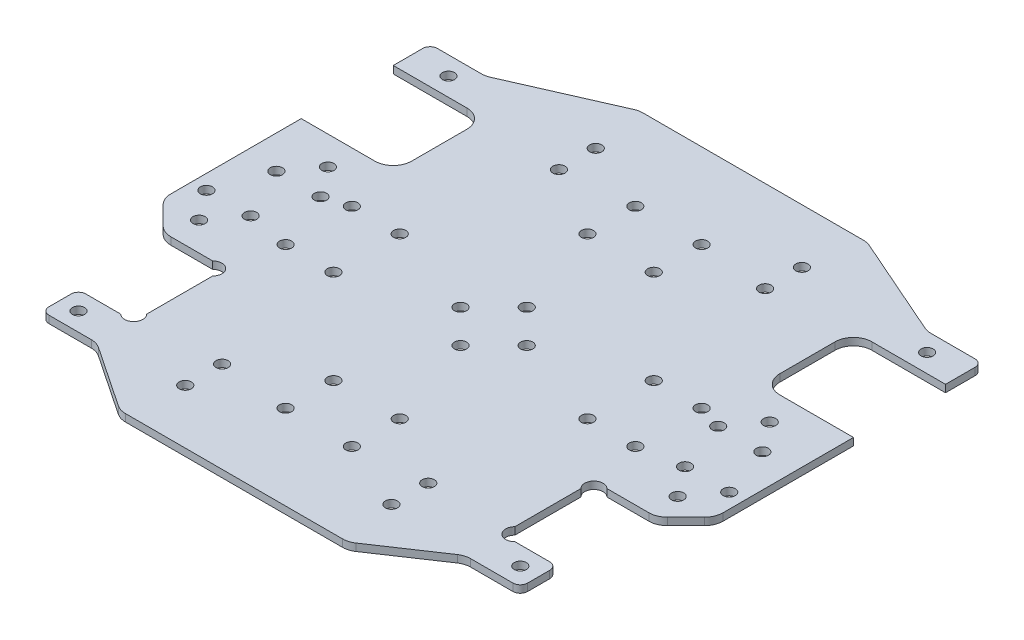
SolidWorks part; units mm, degrees
ref_plane "前视基准面" through (0, 0, 0) normal (0, 0, 1) x (1, 0, 0)
ref_plane "上视基准面" through (0, 0, 0) normal (0, 1, 0) x (1, 0, 0)
ref_plane "右视基准面" through (0, 0, 0) normal (1, 0, 0) x (0, 0, -1)
sketch "草图1" plane through (0, 0, 0) normal (0, 1, 0) x (1, 0, 0)
  line L1 (-75, -70.5) -> (75, -70.5)
  line L2 (-75, -70.5) -> (-75, 70.5)
  line L3 (-75, 70.5) -> (75, 70.5)
  line L4 (75, -70.5) -> (75, 70.5)
  line L5 (-75, -70.5) -> (75, 70.5) construction
  line L6 (-75, 70.5) -> (75, -70.5) construction
  point P0 (0, 0)
  dimension "D1" = 141
  dimension "D2" = 150
extrude "凸台-拉伸1" add sketch "草图1" along normal blind 2
sketch "草图2" plane through (0, 2, 0) normal (0, 1, 0) x (1, 0, 0)
  line L0 (-60, -11) -> (-65, -11) construction
  line L1 (-60, -11) -> (60, -11) construction
  line L2 (-60, -11) -> (-60, 11) construction
  line L3 (-60, 11) -> (60, 11) construction
  line L4 (60, -11) -> (60, 11) construction
  line L5 (-60, -11) -> (60, 11) construction
  line L6 (-60, 11) -> (60, -11) construction
  line L11 (-75, 70.5) -> (-75, -70.5) construction
  line L12 (-66, 7) -> (-54, 7) construction
  line L13 (-71, -15) -> (-59, -15) construction
  line L14 (-66, 7) -> (-66, 15) construction
  line L15 (-66, 15) -> (-54, 15) construction
  line L16 (-54, 7) -> (-54, 15) construction
  line L17 (-66, 7) -> (-54, 15) construction
  line L18 (-66, 15) -> (-54, 7) construction
  line L19 (-71, -15) -> (-71, -7) construction
  line L20 (-71, -7) -> (-59, -7) construction
  line L21 (-59, -15) -> (-59, -7) construction
  line L22 (-71, -15) -> (-59, -7) construction
  line L23 (-71, -7) -> (-59, -15) construction
  circle A4 centre (-60, 15) radius 1.65
  circle A5 centre (-66, 7) radius 1.65
  circle A6 centre (-54, 7) radius 1.65
  circle A7 centre (-71, -7) radius 1.65
  circle A8 centre (-59, -7) radius 1.65
  circle A9 centre (-65, -15) radius 1.65
  point P0 (0, 0)
  point P14 (-60, 0)
  dimension "D5" = 3.3
  dimension "D1" = 12
  dimension "D2" = 8
  dimension "D3" = 15
  dimension "D4" = 15
  dimension "D6" = 5
  dimension "D7" = 8
  dimension "D8" = 12
extrude "切除-拉伸1" cut sketch "草图2" against normal up to next
sketch "草图9" plane through (0, 2, 0) normal (0, 1, 0) x (1, 0, 0)
  line L0 (0, 22.75) -> (0, -22.75) construction
  line L1 (-75, -70.5) -> (-50, -70.5)
  line L2 (-75, -70.5) -> (-75, -22.75)
  line L3 (-75, -22.75) -> (-50, -22.75)
  line L4 (-50, -70.5) -> (-50, -22.75)
  line L5 (75, -70.5) -> (50, -70.5)
  line L6 (75, -70.5) -> (75, -22.75)
  line L7 (75, -22.75) -> (50, -22.75)
  line L8 (50, -70.5) -> (50, -22.75)
  point P14 (0, 0)
  dimension "D1" = 45.5
  dimension "D2" = 100
extrude "切除-拉伸5" cut sketch "草图9" against normal up to next
sketch "草图10" plane through (0, 2, 0) normal (0, 1, 0) x (1, 0, 0)
  line L0 (-75, 70.5) -> (-31, 70.5)
  line L1 (75, 70.5) -> (-75, 70.5) construction
  line L2 (-31, 70.5) -> (-60, 57.75)
  line L3 (-60, 57.75) -> (-75, 57.75)
  line L4 (-75, 70.5) -> (-75, -22.75) construction
  line L5 (-75, 57.75) -> (-75, 70.5)
  line L6 (0, 70.5) -> (-31, 70.5) construction
  dimension "D1" = 15
  dimension "D2" = 12.75
  dimension "D3" = 31
extrude "切除-拉伸6" cut sketch "草图10" against normal up to next
mirror "镜向1" about plane through (0, 0, 0) normal (1, 0, 0) of "切除-拉伸6", "切除-拉伸1"
chamfer "倒角1" distance 8 angle 45 2 edges at (75, 1, 22.75) (-75, 1, 22.75)
sketch "草图11" plane through (0, 2, 0) normal (0, 1, 0) x (1, 0, 0)
  line L0 (-75, 57.75) -> (-75, -14.75) construction
  line L1 (-75, 47.75) -> (-50, 47.75)
  line L2 (-75, 47.75) -> (-75, 22.75)
  line L3 (-75, 22.75) -> (-50, 22.75)
  line L4 (-50, 47.75) -> (-50, 22.75)
  line L5 (-75, 57.75) -> (-60, 57.75) construction
  line L6 (0, 0) -> (0, 70.5) construction
  line L7 (31, 70.5) -> (-31, 70.5) construction
  line L8 (75, 22.75) -> (50, 22.75)
  line L9 (50, 47.75) -> (50, 22.75)
  line L10 (75, 47.75) -> (50, 47.75)
  line L11 (75, 47.75) -> (75, 22.75)
  dimension "D1" = 10
  dimension "D2" = 25
  dimension "D3" = 25
extrude "切除-拉伸7" cut sketch "草图11" against normal up to next
sketch "草图12" plane through (0, 2, 0) normal (0, 1, 0) x (1, 0, 0)
  line L0 (-75, 52.75) -> (-65, 52.75) construction
  line L1 (-75, 57.75) -> (-75, 47.75) construction
  line L2 (0, 0) -> (0, 70.5) construction
  line L3 (31, 70.5) -> (-31, 70.5) construction
  circle A0 centre (-65, 52.75) radius 1.65
  circle A1 centre (65, 52.75) radius 1.65
  dimension "D1" = 3.3
  dimension "D2" = 10
extrude "切除-拉伸8" cut sketch "草图12" against normal up to next
fillet "圆角1" radius 5 8 edges at (75, 1, 14.75) (67, 1, 22.75) (-67, 1, 22.75) (-75, 1, 14.75) (50, 1, -22.75) (50, 1, -47.75) (-50, 1, -22.75) (-50, 1, -47.75)
sketch "草图13" plane through (0, 2, 0) normal (0, 1, 0) x (1, 0, 0)
  line L0 (-50, -70.5) -> (-50, -57.75)
  line L1 (-50, -70.5) -> (-50, -22.75) construction
  line L2 (-50, -57.75) -> (-31, -70.5)
  line L3 (-50, -70.5) -> (50, -70.5) construction
  line L4 (-31, -70.5) -> (-50, -70.5)
  line L5 (31, -70.5) -> (-31, -70.5) construction
  point P11 (0, -70.5)
  dimension "D1" = 12.75
  dimension "D2" = 62
extrude "切除-拉伸9" cut sketch "草图13" against normal up to next
sketch "草图14" plane through (0, 0, 0) normal (0, 1, 0) x (1, 0, 0)
  line L1 (-50, -57.75) -> (-65, -57.75)
  line L2 (-50, -57.75) -> (-50, -47.75)
  line L3 (-50, -47.75) -> (-65, -47.75)
  line L4 (-65, -57.75) -> (-65, -47.75)
  dimension "D1" = 15
  dimension "D2" = 10
extrude "凸台-拉伸2" add sketch "草图14" along normal up to surface (2 mm away) up to face at (-65, 2, -51.1)
sketch "草图15" plane through (0, 2, 0) normal (0, 1, 0) x (1, 0, 0)
  line L0 (-65, -52.75) -> (-60, -52.75) construction
  line L1 (-65, -57.75) -> (-65, -47.75) construction
  circle A0 centre (-60, -52.75) radius 1.65
  dimension "D2" = 3.3
  dimension "D1" = 5
extrude "切除-拉伸10" cut sketch "草图15" against normal up to next
sketch "草图18" plane through (0, 2, 0) normal (0, 1, 0) x (1, 0, 0)
  line L0 (-51.7678, -45.9822) -> (-50, -47.75) construction
  line L1 (-51.7678, -24.5178) -> (-50, -22.75) construction
  line L2 (-50, -47.75) -> (-50, -22.75) construction
  circle A0 centre (-51.7678, -24.5178) radius 2.5
  circle A1 centre (-51.7678, -45.9822) radius 2.5
  dimension "10" = 5
  dimension "D1" = 45
  dimension "D2" = 45
extrude "切除-拉伸13" cut sketch "草图18" against normal up to next
sketch "草图19" plane through (0, 2, 0) normal (0, 1, 0) x (1, 0, 0)
  line L0 (0, 0) -> (-34.5, 0) construction
  line L1 (-34.5, 0) -> (-47.5, 0) construction
  line L2 (-47.5, 9) -> (-47.5, -9) construction
  line L3 (-34.5, 9) -> (-34.5, -9) construction
  line L4 (-47.5, -9) -> (-34.5, -9) construction
  circle A0 centre (-47.5, 9) radius 1.65
  circle A1 centre (-47.5, -9) radius 1.65
  circle A2 centre (-34.5, -9) radius 1.65
  circle A3 centre (-34.5, 9) radius 1.65
  point P6 (-47.5, 0)
  point P10 (-34.5, 0)
  dimension "D2" = 3.3
  dimension "D1" = 18
  dimension "D3" = 47.5
  dimension "D4" = 13
extrude "切除-拉伸14" cut sketch "草图19" against normal up to next
mirror "镜向2" about plane through (0, 0, 0) normal (1, 0, 0) of "切除-拉伸13", "切除-拉伸10", "切除-拉伸9", "凸台-拉伸2"
mirror "镜向4" about plane through (0, 0, 0) normal (1, 0, 0) of "切除-拉伸14"
sketch "草图20" plane through (0, 2, 0) normal (0, 1, 0) x (1, 0, 0)
  line L0 (0, 9) -> (0, -9) construction
  circle A0 centre (0, 9) radius 1.65
  circle A1 centre (0, -9) radius 1.65
  point P4 (0, 0)
  dimension "D2" = 3.3
  dimension "D1" = 18
extrude "切除-拉伸15" cut sketch "草图20" against normal up to next
fillet "圆角2" radius 2 6 edges at (75, 1, -57.75) (-75, 1, -57.75) (65, 1, 57.75) (65, 1, 47.75) (-65, 1, 57.75) (-65, 1, 47.75)
sketch "草图17" plane through (0, 2, 0) normal (0, 1, 0) x (1, 0, 0)
  line L0 (0, 0) -> (0, -50.75) construction
  line L2 (-28, -55.75) -> (28, -55.75) construction
  line L3 (-28, -55.75) -> (-28, -45.75) construction
  line L4 (-28, -45.75) -> (28, -45.75) construction
  line L5 (28, -55.75) -> (28, -45.75) construction
  line L6 (-28, -55.75) -> (28, -45.75) construction
  line L7 (-28, -45.75) -> (28, -55.75) construction
  circle A0 centre (-28, -45.75) radius 1.65
  circle A1 centre (-28, -55.75) radius 1.65
  circle A2 centre (28, -45.75) radius 1.65
  circle A3 centre (28, -55.75) radius 1.65
  dimension "D4" = 3.3
  dimension "D1" = 50.75
  dimension "D2" = 10
  dimension "D3" = 56
extrude "切除-拉伸12" cut sketch "草图17" against normal up to next
mirror "镜向3" about plane through (0, 0, 0) normal (0, 0, 1) of "切除-拉伸12"
fillet "圆角3" radius 5 8 edges at (50, 1, 57.75) (31, 1, 70.5) (-31, 1, 70.5) (-50, 1, 57.75) (60, 1, -57.75) (31, 1, -70.5) (-31, 1, -70.5) (-60, 1, -57.75)
sketch "草图21" plane through (0, 0, 0) normal (0, 0, 1) x (1, 0, 0)
  line L0 (0, 0) -> (0, 2) construction
  line L1 (-29.4778, 2) -> (29.4778, 2) construction
pattern_circular "阵列(圆周)1" count 2 every 90 about axis through (0, 0, 0) along (0, 1, 0) of "镜向4", "切除-拉伸15", "切除-拉伸14"
sketch "草图22" plane through (0, 2, 0) normal (0, 1, 0) x (1, 0, 0)
  line L0 (-40, -26.2855) -> (-40, -47.75)
  line L1 (-40, -47.75) -> (-8.1802, -15.9302)
  line L2 (-8.1802, -15.9302) -> (-18.9124, -5.198)
  line L3 (-18.9124, -5.198) -> (-40, -26.2855)
  line L4 (-50, -44.2145) -> (-50, -26.2855) construction
  line L5 (-63, -47.75) -> (-53.5355, -47.75) construction
  line L6 (-50, -26.2855) -> (-40, -26.2855) construction
  dimension "D1" = 45
  dimension "D2" = 10
  dimension "D3" = 45
sketch "草图23" plane through (0, 2, 0) normal (0, 1, 0) x (1, 0, 0)
  line L0 (-50, -47.75) -> (-50, -22.75) construction
  line L1 (-50, -22.75) -> (-47.5, -9) construction
  line L2 (-47.5, -9) -> (-34.5, -9) construction
  line L3 (-34.5, -9) -> (-9, 0) construction
  line L4 (-9, 0) -> (0, -9) construction
  line L5 (0, -9) -> (-9, -34.5) construction
  line L6 (-9, -34.5) -> (-28, -45.75) construction
  line L7 (-28, -45.75) -> (-50, -47.75) construction
  line L8 (-29.5765, -40.8727) -> (-45, -42.2748)
  line L9 (-45, -42.2748) -> (-45, -23.2008)
  line L10 (-45, -23.2008) -> (-43.3271, -14)
  line L11 (-43.3271, -14) -> (-33.6435, -14)
  line L12 (-33.6435, -14) -> (-10.3074, -5.7637)
  line L13 (-10.3074, -5.7637) -> (-5.7637, -10.3074)
  line L14 (-5.7637, -10.3074) -> (-13.1104, -31.1231)
  line L15 (-13.1104, -31.1231) -> (-29.5765, -40.8727)
  line L16 (-28, 45.75) -> (-9, 34.5) construction
  line L17 (-9, 34.5) -> (0, 9) construction
  line L18 (0, 9) -> (-9, 0) construction
  line L19 (-9, 0) -> (-34.5, 9) construction
  line L20 (-34.5, 9) -> (-47.5, 9) construction
  line L21 (-47.5, 9) -> (-50, 27.75) construction
  line L22 (-50, 27.75) -> (-50, 42.75) construction
  line L23 (-50, 42.75) -> (-28, 45.75) construction
  line L24 (-45, 38.3855) -> (-29.0494, 40.5606)
  line L25 (-29.0494, 40.5606) -> (-13.1104, 31.1231)
  line L26 (-13.1104, 31.1231) -> (-5.7637, 10.3074)
  line L27 (-5.7637, 10.3074) -> (-10.3074, 5.7637)
  line L28 (-10.3074, 5.7637) -> (-33.6435, 14)
  line L29 (-33.6435, 14) -> (-43.1224, 14)
  line L30 (-43.1224, 14) -> (-45, 28.0819)
  line L31 (-45, 28.0819) -> (-45, 38.3855)
  arc A0 (-53.5355, -47.75) -> (-50, -44.2145) centre (-51.7678, -45.9822) ccw construction
  arc A1 (-50, -26.2855) -> (-53.5355, -22.75) centre (-51.7678, -24.5178) ccw construction
  arc A2 (-55, 22.75) -> (-50, 27.75) centre (-55, 27.75) ccw construction
  dimension "D1" = 5
  dimension "D2" = 5
extrude "切除-拉伸16" [suppressed] cut sketch "草图23" against normal up to next
mirror "镜向5" [suppressed] about plane through (0, 0, 0) normal (1, 0, 0)
